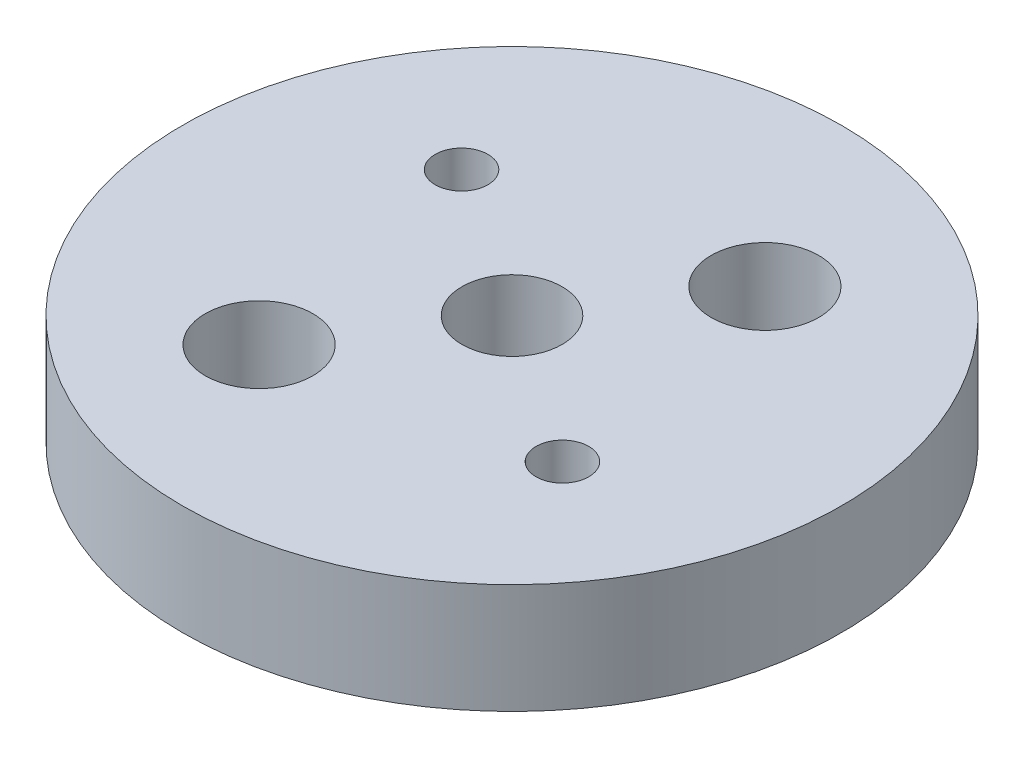
SolidWorks part; units mm, degrees
material "6061-T6 (SS)"
ref_plane "Front Plane" through (0, 0, 0) normal (0, 0, 1) x (1, 0, 0)
ref_plane "Top Plane" through (0, 0, 0) normal (0, 1, 0) x (1, 0, 0)
ref_plane "Right Plane" through (0, 0, 0) normal (1, 0, 0) x (0, 0, -1)
sketch "Sketch1" plane through (0, 0, 0) normal (0, 1, 0) x (1, 0, 0)
  circle A0 centre (0, 0) radius 19.05
  circle A1 centre (0, 0) radius 2.8956
  circle A3 centre (8.7673, -5.8521) radius 1.524
  circle A4 centre (0, 0) radius 10.541 construction
  circle A5 centre (-8.7673, 5.8521) radius 1.524
  circle A7 centre (5.8521, 8.7673) radius 3.1115
  circle A8 centre (-5.8521, -8.7673) radius 3.1115
  circle A9 centre (5.8521, 8.7673) radius 1.524 [skipped]
  circle A10 centre (-5.8521, -8.7673) radius 1.524 [skipped]
  point P18 (0, 0)
  dimension "D1" = 38.1
  dimension "D2" = 5.7912
  dimension "D3" = 4
  dimension "D4" = 6.223
  dimension "D5" = 3.048
  dimension "D6" = 6.223
extrude "Boss-Extrude1" add sketch "Sketch1" along normal blind 6.35
